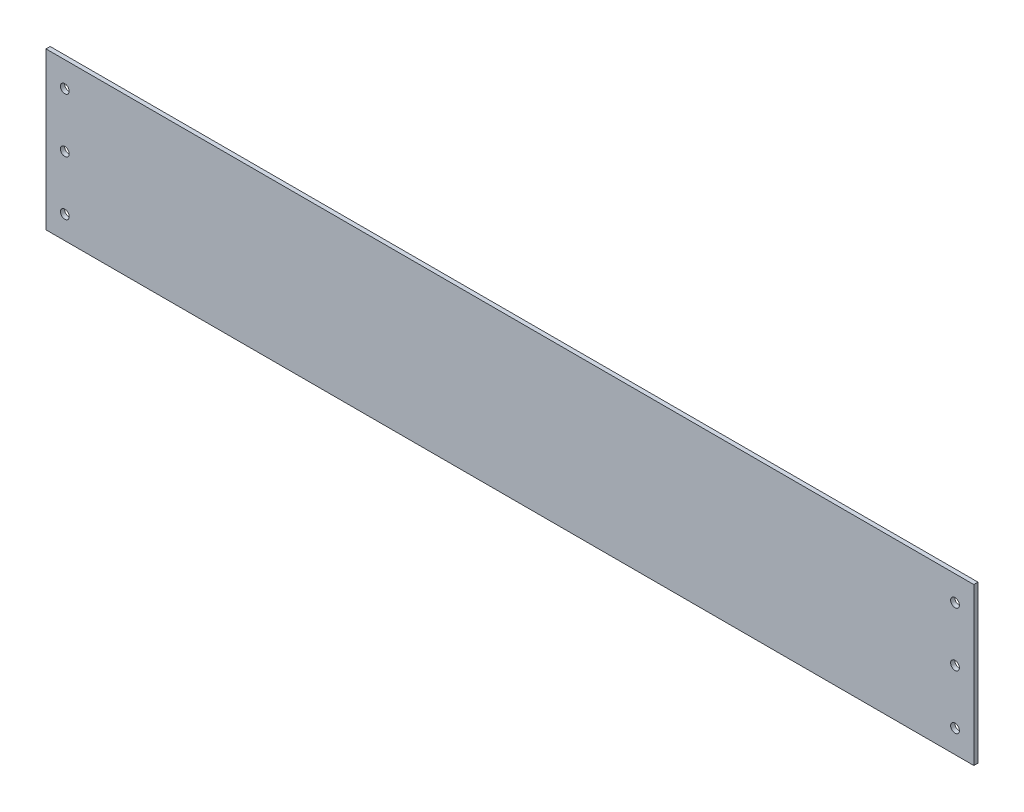
SolidWorks part; units mm, degrees
material "Д16Т ГОСТ 4784-74"
ref_plane "Спереди" through (0, 0, 0) normal (0, 0, 1) x (1, 0, 0)
ref_plane "Сверху" through (0, 0, 0) normal (0, 1, 0) x (1, 0, 0)
ref_plane "Справа" through (0, 0, 0) normal (1, 0, 0) x (0, 0, -1)
sketch "Эскиз1" plane through (0, 0, 0) normal (0, 0, 1) x (1, 0, 0)
  line L0 (111, 37.5) -> (111, 0) construction
  line L1 (0, 0) -> (222, 0)
  line L2 (0, 0) -> (0, 37.5)
  line L3 (0, 37.5) -> (222, 37.5)
  line L4 (222, 0) -> (222, 37.5)
  line L5 (-5.3624, -0.5) -> (33.9363, -0.5) construction
  line L6 (4.5, 37.5) -> (4.5, 31.5) construction
  line L7 (4.5, 31.5) -> (4.5, 18.5) construction
  line L8 (4.5, 18.5) -> (4.5, 5.5) construction
  line L9 (4.5, 5.5) -> (4.5, -0.5) construction
  line L10 (217.5, 5.5) -> (217.5, -0.5) construction
  line L11 (217.5, 18.5) -> (217.5, 5.5) construction
  line L12 (217.5, 31.5) -> (217.5, 18.5) construction
  line L13 (217.5, 37.5) -> (217.5, 31.5) construction
  circle A0 centre (4.5, 31.5) radius 1.05
  circle A1 centre (4.5, 18.5) radius 1.05
  circle A2 centre (4.5, 5.5) radius 1.05
  circle A3 centre (217.5, 5.5) radius 1.05
  circle A4 centre (217.5, 18.5) radius 1.05
  circle A5 centre (217.5, 31.5) radius 1.05
  dimension "D4" = 13
  dimension "D6" = 2.1
  dimension "D1" = 222
  dimension "D2" = 1
  dimension "D3" = 38
  dimension "D5" = 4.5
extrude "Бобышка-Вытянуть1" add sketch "Эскиз1" along normal blind 1
